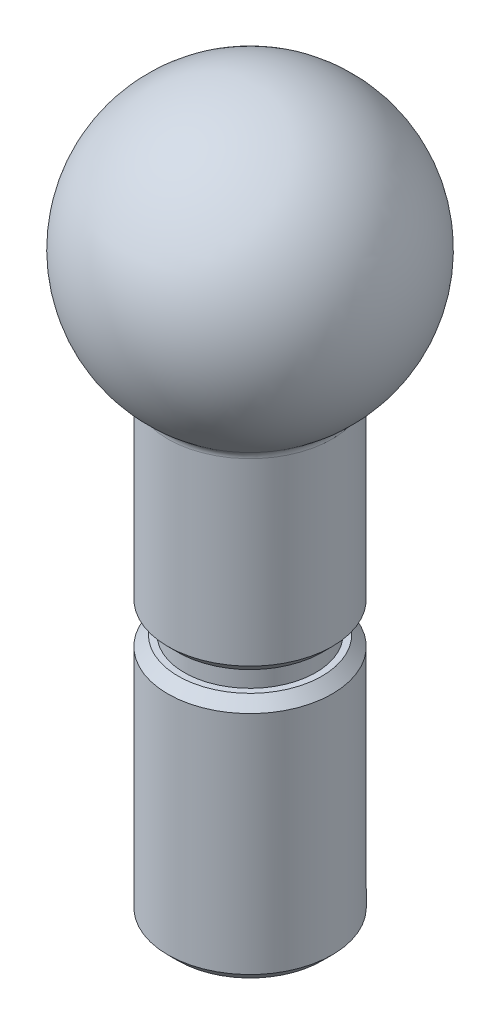
SolidWorks part; units mm, degrees
ref_plane "Front Plane" through (0, 0, 0) normal (0, 0, 1) x (1, 0, 0)
ref_plane "Top Plane" through (0, 0, 0) normal (0, 1, 0) x (1, 0, 0)
ref_plane "Right Plane" through (0, 0, 0) normal (1, 0, 0) x (0, 0, -1)
sketch "Sketch1" plane through (0, 0, 0) normal (0, 0, 1) x (1, 0, 0)
  line L0 (0, 0) -> (0, -86852.2397) construction
  line L1 (40, -57.4456) -> (40, -282.4456)
  line L2 (40, -282.4456) -> (0, -282.4456)
  line L3 (0, -282.4456) -> (0, 70)
  arc A0 (40, -57.4456) -> (0, 70) centre (0, 0) ccw
  dimension "D1" = 140
  dimension "D2" = 225
  dimension "D3" = 40
revolve "Revolve1" add sketch "Sketch1" angle 360 about L0
ref_plane "Plane1" through (0, -162.4456, 0) normal (0, -1, 0) x (-1, 0, 0)
sketch "Sketch2" plane through (0, -162.4456, 0) normal (0, -1, 0) x (-1, 0, 0)
  circle A0 centre (0, 0) radius 40
  circle A1 centre (0, 0) radius 32
  dimension "D1" = 80
  dimension "D2" = 64
extrude "Cut-Extrude1" cut sketch "Sketch2" against normal blind 10
fillet "Fillet1" radius 5 1 edges at (0, -57.4456, 40)
chamfer "Chamfer1" distance 5 angle 45 3 edges at (0, -282.4456, 40) (0, -162.4456, -40) (0, -152.4456, -40)
sketch "Sketch3" plane through (0, -282.4456, 0) normal (0, -1, 0) x (1, 0, 0)
  circle A0 centre (0, 0) radius 40
  dimension "D1" = 80
